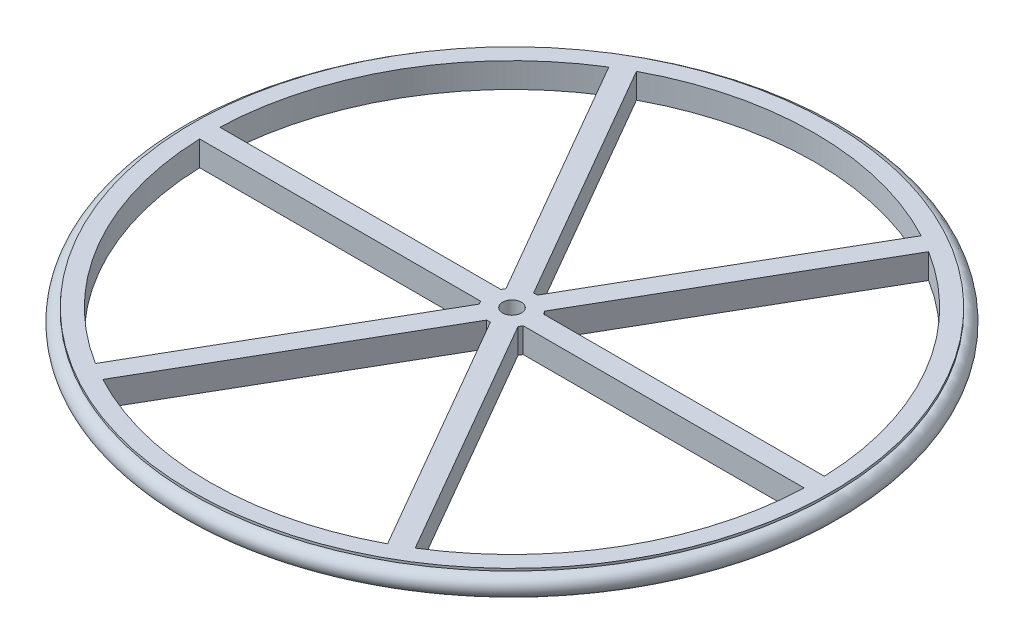
SolidWorks part; units mm, degrees
ref_plane "Front Plane" through (0, 0, 0) normal (0, 0, 1) x (1, 0, 0)
ref_plane "Top Plane" through (0, 0, 0) normal (0, 1, 0) x (1, 0, 0)
ref_plane "Right Plane" through (0, 0, 0) normal (1, 0, 0) x (0, 0, -1)
sketch "Sketch1" plane through (0, 0, 0) normal (0, 1, 0) x (1, 0, 0)
  line L0 (-135.7, 0) -> (135.7, 0) construction
  line L1 (0, -135.7) -> (0, 135.7) construction
  line L2 (-9.0283, 4.3) -> (-128.4, 4.3)
  line L3 (-9.0283, -4.3) -> (-128.4, -4.3)
  line L4 (-0.7902, 9.9687) -> (-60.4761, 113.3477)
  line L5 (-8.2381, 5.6687) -> (-67.9239, 109.0477)
  line L6 (8.2381, 5.6687) -> (67.9239, 109.0477)
  line L7 (0.7902, 9.9687) -> (60.4761, 113.3477)
  line L8 (9.0283, -4.3) -> (128.4, -4.3)
  line L9 (9.0283, 4.3) -> (128.4, 4.3)
  line L10 (0.7902, -9.9687) -> (60.4761, -113.3477)
  line L11 (8.2381, -5.6687) -> (67.9239, -109.0477)
  line L12 (-8.2381, -5.6687) -> (-67.9239, -109.0477)
  line L13 (-0.7902, -9.9687) -> (-60.4761, -113.3477)
  circle A0 centre (0, 0) radius 4
  arc A1 (9.0283, 4.3) -> (8.2381, 5.6687) centre (0, 0) ccw
  circle A2 centre (0, 0) radius 135.7 construction
  arc A3 (-67.9239, 109.0477) -> (-128.4, 4.3) centre (0, 0) ccw
  arc A4 (60.4761, 113.3477) -> (-60.4761, 113.3477) centre (0, 0) ccw
  arc A5 (67.9239, 109.0477) -> (128.4, 4.3) centre (0, 0) cw
  arc A6 (128.4, -4.3) -> (67.9239, -109.0477) centre (0, 0) cw
  arc A7 (60.4761, -113.3477) -> (-60.4761, -113.3477) centre (0, 0) cw
  arc A8 (-128.4, -4.3) -> (-67.9239, -109.0477) centre (0, 0) ccw
  circle A9 centre (0, 0) radius 135.7
  arc A10 (0.7902, 9.9687) -> (-0.7902, 9.9687) centre (0, 0) ccw
  arc A11 (-8.2381, 5.6687) -> (-9.0283, 4.3) centre (0, 0) ccw
  arc A12 (-9.0283, -4.3) -> (-8.2381, -5.6687) centre (0, 0) ccw
  arc A13 (-0.7902, -9.9687) -> (0.7902, -9.9687) centre (0, 0) ccw
  arc A14 (8.2381, -5.6687) -> (9.0283, -4.3) centre (0, 0) ccw
  point P35 (0, 0)
  dimension "D1" = 8
  dimension "D2" = 20
  dimension "D3" = 271.4
  dimension "D4" = 8.6
  dimension "D5" = 128.4
  dimension "D6" = 6
extrude "Boss-Extrude1" add sketch "Sketch1" along normal blind 10.6
sketch "Sketch3" plane through (0, 0, 0) normal (0, 0, 1) x (1, 0, 0)
  line L1 (0, 0) -> (0, 16.7475) construction
  line L3 (135.7, 0) -> (135.7, 10.6) construction
  circle A1 centre (135.7, 5.3) radius 4.3
  dimension "D1" = 8.6
revolve "Cut-Revolve1" cut sketch "Sketch3" angle 360 about L1
sketch "Sketch5" plane through (0, 0, 0) normal (1, 0, 0) x (0, 0, -1)
  line L0 (0, 0) -> (0, 29.9636) construction
  line L1 (-135.7, 0) -> (135.7, 0) construction
  circle A0 centre (135.7, 5.3) radius 4.3
  dimension "D1" = 8.6
revolve "Revolve1" add sketch "Sketch5" angle 360 about L0
